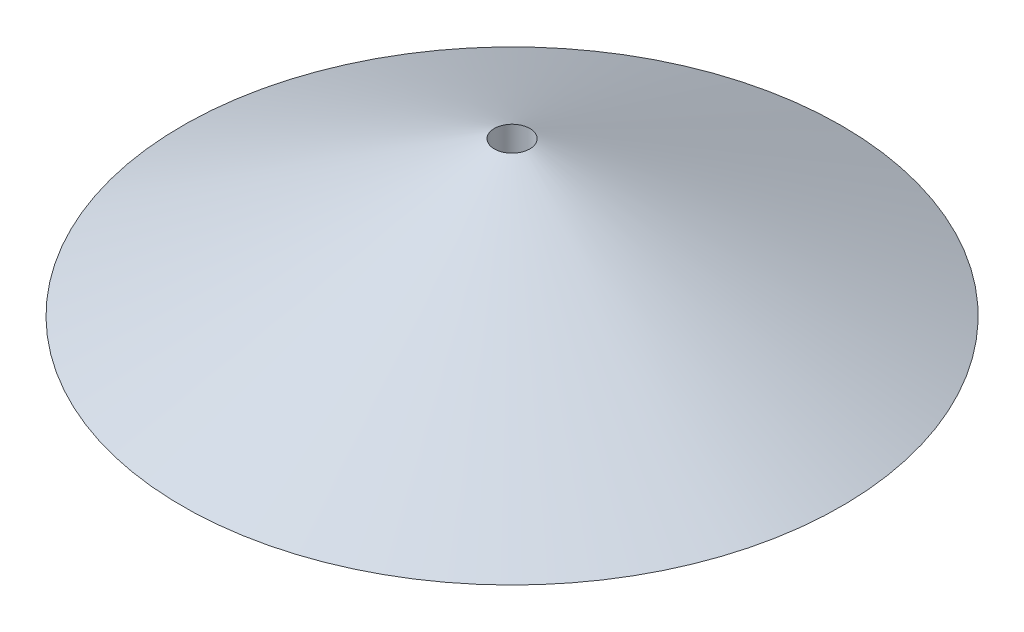
SolidWorks part; units mm, degrees
ref_plane "Front Plane" through (0, 0, 0) normal (0, 0, 1) x (1, 0, 0)
ref_plane "Top Plane" through (0, 0, 0) normal (0, 1, 0) x (1, 0, 0)
ref_plane "Right Plane" through (0, 0, 0) normal (1, 0, 0) x (0, 0, -1)
sketch "Sketch3" plane through (0, 0, 0) normal (1, 0, 0) x (0, 0, -1)
  line L1 (0, 0) -> (32.5, 0)
  line L2 (0, 16) -> (32.5, 0)
  line L3 (0, 0) -> (0, 16)
  dimension "D1" = 32.5
  dimension "D3" = 16
revolve "Revolve5" add sketch "Sketch3" angle 360 about L3
sketch "Sketch4" plane through (0, 0, 0) normal (0, -1, 0) x (1, 0, 0)
  circle A0 centre (0, 0) radius 1.75
  dimension "D1" = 3.5
extrude "Cut-Extrude1" cut sketch "Sketch4" against normal through all
